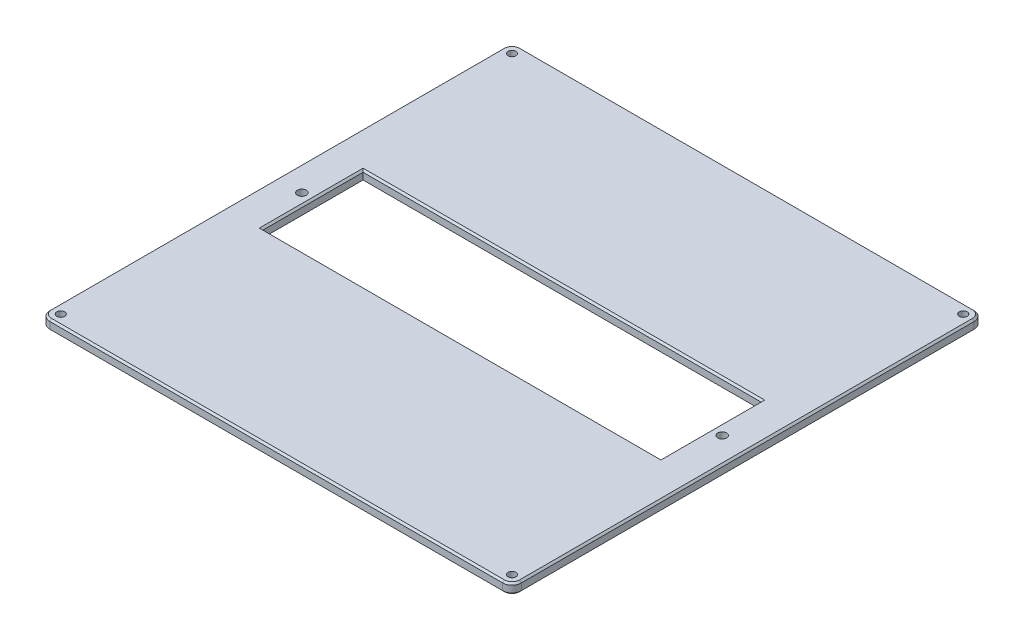
SolidWorks part; units mm, degrees
ref_plane "Front Plane" through (0, 0, 0) normal (0, 0, 1) x (1, 0, 0)
ref_plane "Top Plane" through (0, 0, 0) normal (0, 1, 0) x (1, 0, 0)
ref_plane "Right Plane" through (0, 0, 0) normal (1, 0, 0) x (0, 0, -1)
sketch "Sketch1" plane through (0, 0, 0) normal (0, 1, 0) x (1, 0, 0)
  line L1 (-133.35, 133.35) -> (133.35, 133.35)
  line L2 (-133.35, 133.35) -> (-133.35, -133.35)
  line L3 (-133.35, -133.35) -> (133.35, -133.35)
  line L4 (133.35, 133.35) -> (133.35, -133.35)
  line L5 (-133.35, 133.35) -> (133.35, -133.35) construction
  line L6 (-133.35, -133.35) -> (133.35, 133.35) construction
  line L7 (-112.6, -28.35) -> (112.6, -28.35)
  line L8 (-112.6, -28.35) -> (-112.6, 28.35)
  line L9 (-112.6, 28.35) -> (112.6, 28.35)
  line L10 (112.6, -28.35) -> (112.6, 28.35)
  line L11 (-112.6, -28.35) -> (112.6, 28.35) construction
  line L12 (-112.6, 28.35) -> (112.6, -28.35) construction
  circle A0 centre (-127.625, 127.625) radius 2.225
  circle A1 centre (127.625, 127.625) radius 2.225
  circle A2 centre (127.625, -127.625) radius 2.225
  circle A3 centre (-127.625, -127.625) radius 2.225
  circle A4 centre (118.9, 0) radius 2.5
  circle A5 centre (-118.9, 0) radius 2.5
  point P0 (0, 0)
  point P19 (0, 0)
  dimension "D2" = 5.725
  dimension "D3" = 4.45
  dimension "D6" = 5
  dimension "D7" = 6.3
  dimension "D1" = 266.7
  dimension "D4" = 105
  dimension "D5" = 20.75
  dimension "D8" = 6.3
extrude "Boss-Extrude1" add sketch "Sketch1" along normal blind 5.8
fillet "Fillet1" radius 5.25 4 edges at (-133.35, 2.9, -133.35) (133.35, 2.9, -133.35) (133.35, 2.9, 133.35) (-133.35, 2.9, 133.35)
chamfer "Chamfer1" distance 1 angle 45 24 edges at (-112.6, 0, 0) (0, 0, 28.35) (112.6, 0, 0) (0, 0, -28.35) (112.6, 5.8, 0) (0, 5.8, 28.35) (-112.6, 5.8, 0) (0, 5.8, -28.35) (0, 0, -133.35) (-131.8123, 0, -131.8123) (131.8123, 0, -131.8123) (-133.35, 0, 0) (133.35, 0, 0) (-131.8123, 0, 131.8123) (131.8123, 0, 131.8123) (0, 0, 133.35) (0, 5.8, -133.35) (-131.8123, 5.8, -131.8123) (131.8123, 5.8, -131.8123) (-133.35, 5.8, 0) (133.35, 5.8, 0) (-131.8123, 5.8, 131.8123) (131.8123, 5.8, 131.8123) (0, 5.8, 133.35)
